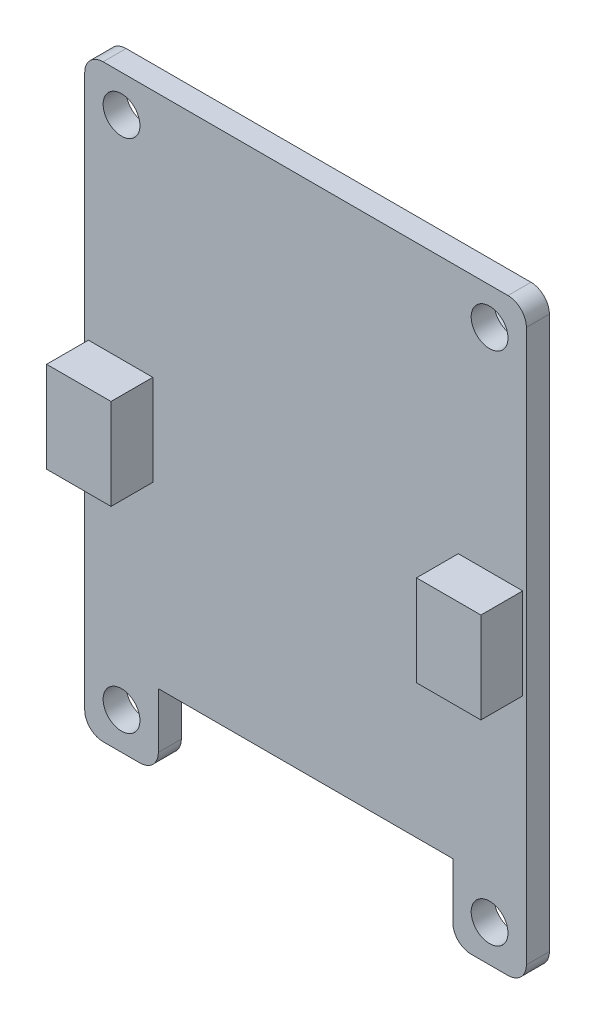
SolidWorks part; units mm, degrees
ref_plane "Front Plane" through (0, 0, 0) normal (0, 0, 1) x (1, 0, 0)
ref_plane "Top Plane" through (0, 0, 0) normal (0, 1, 0) x (1, 0, 0)
ref_plane "Right Plane" through (0, 0, 0) normal (1, 0, 0) x (0, 0, -1)
sketch "Sketch1" plane through (0, 0, 0) normal (0, 0, 1) x (1, 0, 0)
  line L0 (-15.24, 20.32) -> (15.24, 20.32)
  line L1 (15.24, 20.32) -> (15.24, -20.32)
  line L2 (15.24, -20.32) -> (10.16, -20.32)
  line L3 (10.16, -20.32) -> (10.16, -15.24)
  line L4 (10.16, -15.24) -> (-10.16, -15.24)
  line L5 (-10.16, -15.24) -> (-10.16, -20.32)
  line L6 (-10.16, -20.32) -> (-15.24, -20.32)
  line L7 (-15.24, -20.32) -> (-15.24, 20.32)
  circle A0 centre (-12.7, -17.78) radius 1.27
  circle A1 centre (12.7, -17.78) radius 1.27
  circle A2 centre (-12.7, 17.78) radius 1.27
  circle A3 centre (12.7, 17.78) radius 1.27
  point P2 (0, 20.32)
  point P9 (-15.24, 0)
  point P20 (-10.16, -17.78)
  point P23 (-12.7, -20.32)
  point P30 (12.7, -20.32)
  dimension "D5" = 2.54
  dimension "D1" = 40.64
  dimension "D2" = 30.48
  dimension "D3" = 35.56
  dimension "D4" = 5.08
  dimension "D6" = 35.56
extrude "Boss-Extrude1" add sketch "Sketch1" along normal blind 1.5875
fillet "Fillet1" radius 1.27 6 edges at (-15.24, 20.32, 0.7937) (-15.24, -20.32, 0.7937) (15.24, -20.32, 0.7937) (15.24, 20.32, 0.7937) (10.16, -20.32, 0.7937) (-10.16, -20.32, 0.7937)
sketch "Sketch2" plane through (0, 0, 0) normal (0, 0, -1) x (-1, 0, 0)
  line L1 (-12.827, -15.24) -> (12.827, -15.24)
  line L2 (12.827, -15.24) -> (12.827, 15.24)
  line L3 (12.827, 15.24) -> (-12.827, 15.24)
  line L4 (-12.827, 15.24) -> (-12.827, -15.24)
  line L5 (10.16, -15.24) -> (-10.16, -15.24) construction
  point P0 (0, 15.24)
  dimension "D1" = 30.48
  dimension "D2" = 25.654
extrude "Boss-Extrude2" add sketch "Sketch2" along normal blind 2.3749
sketch "Sketch3" plane through (0, 0, 1.5875) normal (0, 0, 1) x (1, 0, 0)
  line L0 (11.43, -20.32) -> (13.97, -20.32) construction
  line L1 (-14.986, 3.175) -> (-10.541, 3.175)
  line L2 (-14.986, 3.175) -> (-14.986, -3.0988)
  line L3 (-14.986, -3.0988) -> (-10.541, -3.0988)
  line L4 (-10.541, 3.175) -> (-10.541, -3.0988)
  line L5 (-14.986, 3.175) -> (-10.541, -3.0988) construction
  line L6 (-14.986, -3.0988) -> (-10.541, 3.175) construction
  line L7 (10.541, 3.175) -> (14.986, 3.175)
  line L8 (10.541, 3.175) -> (10.541, -3.0988)
  line L9 (10.541, -3.0988) -> (14.986, -3.0988)
  line L10 (14.986, 3.175) -> (14.986, -3.0988)
  line L11 (10.541, 3.175) -> (14.986, -3.0988) construction
  line L12 (10.541, -3.0988) -> (14.986, 3.175) construction
  line L13 (15.24, -19.05) -> (15.24, 19.05) construction
  line L14 (-15.24, 19.05) -> (-15.24, -19.05) construction
  point P0 (-12.7635, 0.0381)
  point P5 (12.7635, 0.0381)
  dimension "D1" = 6.2738
  dimension "D2" = 23.495
  dimension "D3" = 4.445
  dimension "D4" = 0.254
  dimension "D5" = 0.254
extrude "Boss-Extrude3" add sketch "Sketch3" along normal blind 2.8829
